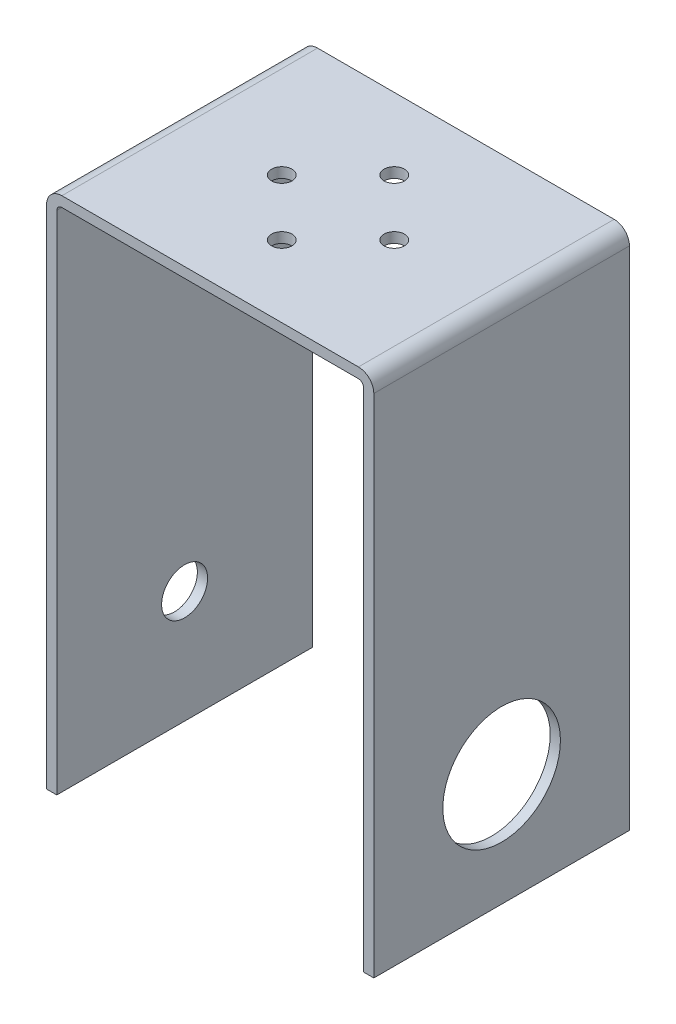
SolidWorks part; units mm, degrees
ref_plane "Front Plane" through (0, 0, 0) normal (0, 0, 1) x (1, 0, 0)
ref_plane "Top Plane" through (0, 0, 0) normal (0, 1, 0) x (1, 0, 0)
ref_plane "Right Plane" through (0, 0, 0) normal (1, 0, 0) x (0, 0, -1)
sketch "Sketch1" plane through (0, 0, 0) normal (0, 0, 1) x (1, 0, 0)
  line L0 (-32, -50) -> (-32, 52)
  line L1 (-32, 52) -> (32, 52)
  line L2 (-30, -50) -> (-30, 50)
  line L3 (-30, 50) -> (30, 50)
  line L4 (30, -50) -> (30, 50)
  line L5 (-30, -50) -> (30, 50) construction
  line L6 (-30, 50) -> (30, -50) construction
  line L7 (32, -50) -> (32, 52)
  line L8 (-32, -50) -> (-30, -50)
  line L9 (30, -50) -> (32, -50)
  point P0 (0, 0)
  dimension "D1" = 100
  dimension "D3" = 60
  dimension "D4" = 2
extrude "Boss-Extrude1" add sketch "Sketch1" along normal blind 50
fillet "Fillet1" radius 1 2 edges at (30, 50, 25) (-30, 50, 25)
fillet "Fillet2" radius 3 2 edges at (32, 52, 25) (-32, 52, 25)
sketch "Sketch2" plane through (0, 52, 0) normal (0, 1, 0) x (1, 0, 0)
  line L0 (0, 0) -> (0, -50) construction
  line L1 (29, -50) -> (-29, -50) construction
  circle A0 centre (0, -25) radius 11 construction
  circle A1 centre (0, -14) radius 2
  circle A2 centre (11, -25) radius 2
  circle A3 centre (0, -36) radius 2
  circle A4 centre (-11, -25) radius 2
  dimension "D1" = 22
  dimension "D2" = 4
extrude "Cut-Extrude1" cut sketch "Sketch2" against normal blind 10
sketch "Sketch4" plane through (32, 0, 0) normal (1, 0, 0) x (0, 0, -1)
  line L0 (-25, 49) -> (-25, -50) construction
  line L1 (0, 49) -> (-50, 49) construction
  line L2 (-50, -50) -> (0, -50) construction
  circle A0 centre (-25, -28) radius 11.5
  dimension "D2" = 23
  dimension "D1" = 22
extrude "Cut-Extrude3" cut sketch "Sketch4" against normal blind 17
sketch "Sketch5" plane through (-30, 0, 0) normal (1, 0, 0) x (0, 0, -1)
  line L0 (-25, -16.5) -> (-25, -39.5) construction
  circle A0 centre (-25, -28) radius 11.5 construction
  circle A1 centre (-25, -28) radius 4.5
  dimension "D1" = 9
extrude "Cut-Extrude4" cut sketch "Sketch5" against normal blind 3
